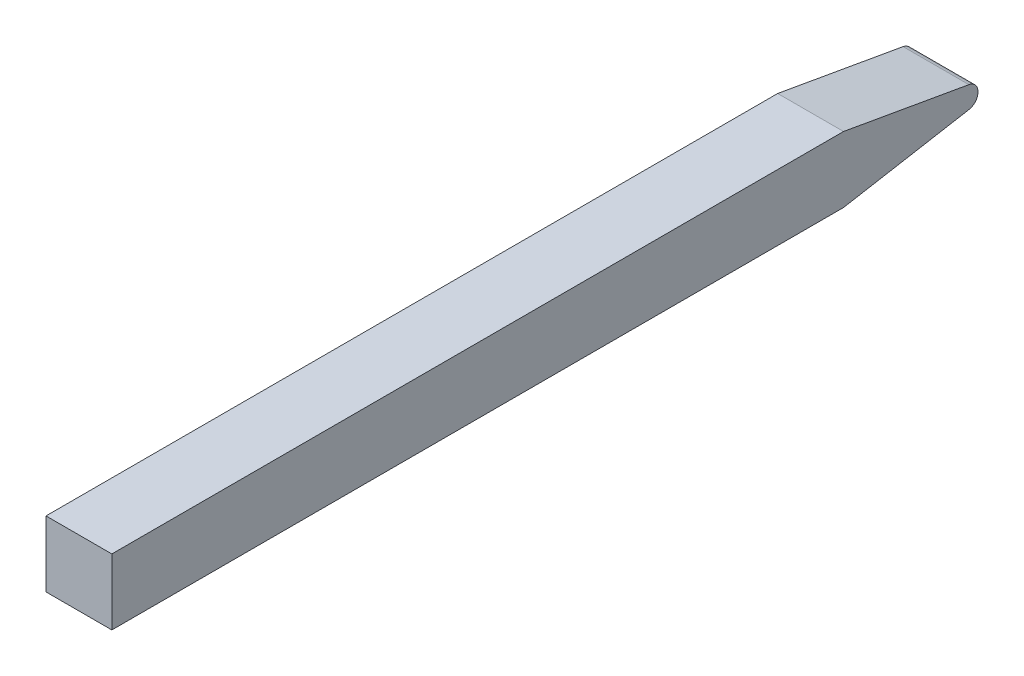
SolidWorks part; units mm, degrees
ref_plane "Front Plane" through (0, 0, 0) normal (0, 0, 1) x (1, 0, 0)
ref_plane "Top Plane" through (0, 0, 0) normal (0, 1, 0) x (1, 0, 0)
ref_plane "Right Plane" through (0, 0, 0) normal (1, 0, 0) x (0, 0, -1)
sketch "Sketch1" plane through (0, 0, 0) normal (1, 0, 0) x (0, 0, -1)
  line L0 (0, 0) -> (2.5521, 0.45)
  line L1 (2.5521, 0.45) -> (0, 0.9)
  line L2 (0, 0.9) -> (-10, 0.9)
  line L3 (-10, 0.9) -> (-10, 0)
  line L4 (-10, 0) -> (0, 0)
  point P3 (12.4298, 1.5)
  point P7 (6.0499, 1.5)
  point P8 (2.5702, 1.0798)
  point P9 (2.6219, 1.5)
  point P10 (4.3582, 0.7685)
  point P11 (0.3981, 1.5)
  point P12 (4.157, 1.2972)
  dimension "D2" = 0.9
  dimension "D3" = 20
  dimension "D5" = 10
extrude "Boss-Extrude1" add sketch "Sketch1" along normal mid plane 0.9
fillet "Fillet1" radius 0.15 1 edges at (0, 0.45, -2.5521)
